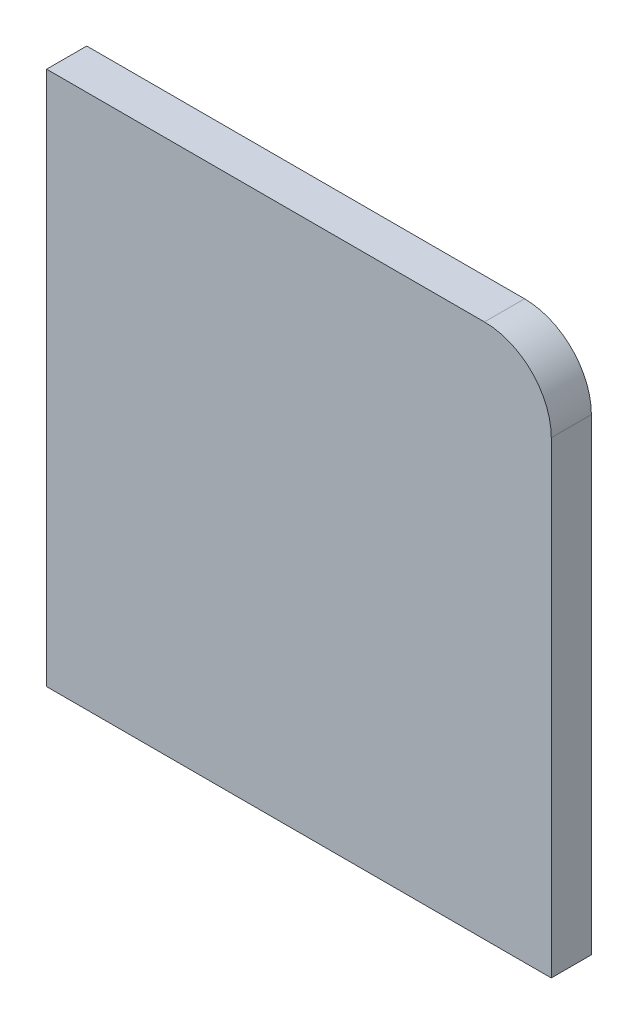
SolidWorks part; units mm, degrees
ref_plane "Plan de face" through (0, 0, 0) normal (0, 0, 1) x (1, 0, 0)
ref_plane "Plan de dessus" through (0, 0, 0) normal (0, 1, 0) x (1, 0, 0)
ref_plane "Plan de droite" through (0, 0, 0) normal (1, 0, 0) x (0, 0, -1)
sketch "Esquisse1" plane through (0, 0, 0) normal (0, 0, 1) x (1, 0, 0)
  line L1 (-30, 50) -> (45.5, 50)
  line L2 (-30, 50) -> (-30, -30)
  line L3 (-30, -30) -> (45.5, -30)
  line L4 (45.5, 50) -> (45.5, -30)
  dimension "D1" = 80
  dimension "D2" = 75.5
extrude "Extrusion1" add sketch "Esquisse1" along normal blind 6
fillet "Congé1" radius 10 1 edges at (45.5, 50, 3)
